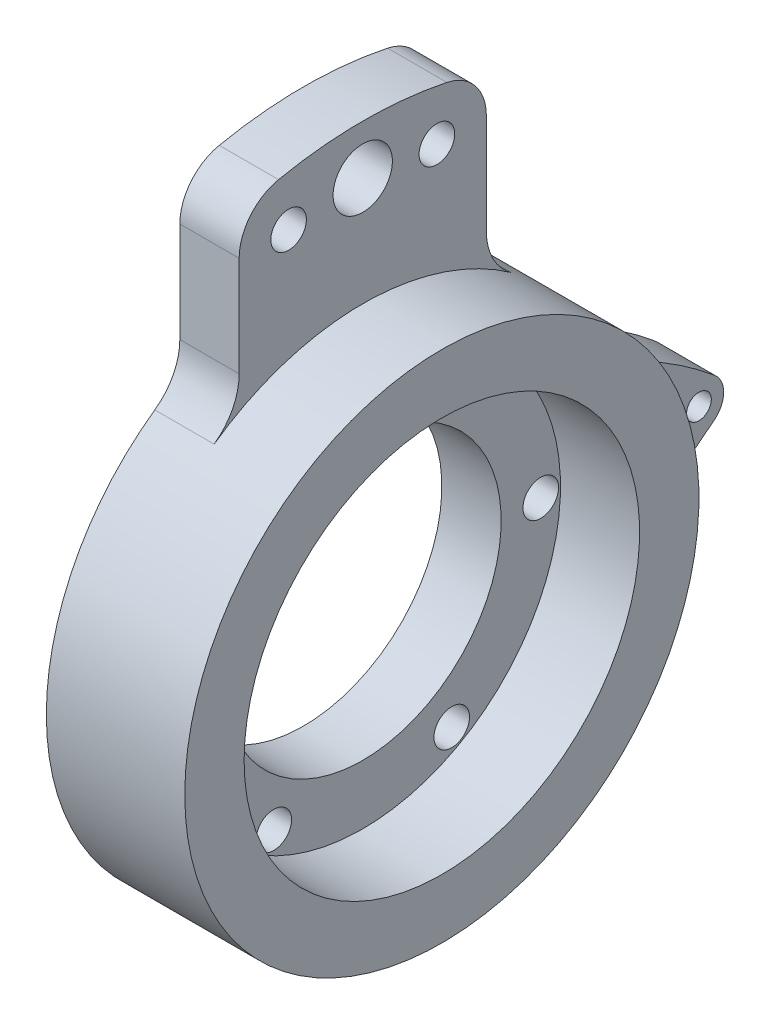
SolidWorks part; units mm, degrees
material "ABS"
ref_plane "Front Plane" through (0, 0, 0) normal (0, 0, 1) x (1, 0, 0)
ref_plane "Top Plane" through (0, 0, 0) normal (0, 1, 0) x (1, 0, 0)
ref_plane "Right Plane" through (0, 0, 0) normal (1, 0, 0) x (0, 0, -1)
sketch "Sketch1" plane through (0, 0, 0) normal (0, 0, 1) x (1, 0, 0)
  line L0 (0, 14) -> (6, 14)
  line L1 (6, 14) -> (6, 20)
  line L2 (6, 20) -> (14, 20)
  line L3 (14, 20) -> (14, 26)
  line L4 (14, 26) -> (0, 26)
  line L5 (0, 26) -> (0, 14)
  line L6 (-2.2572, 0) -> (2.2572, 0) construction
revolve "Revolve1" add sketch "Sketch1" angle 360 about L6
sketch "Sketch3" plane through (0, 0, 0) normal (1, 0, 0) x (0, 0, -1)
  arc A0 (24, -10) -> (26.0687, -7.8828) centre (27.6923, -11.5385) cw
  arc A1 (26.0687, -7.8828) -> (24, -10) centre (27.6923, -11.5385) ccw construction
  arc A2 (26.0687, -7.8828) -> (35.6111, -1.9116) centre (9.8328, 28.6739) ccw
  arc A5 (26.0687, -7.8828) -> (35.6111, -1.9116) centre (9.8328, 28.6739) ccw construction
  arc A6 (35.6111, -1.9116) -> (35.6111, 1.9116) centre (34, 0) ccw
  circle A7 centre (34, 0) radius 2.5 construction
  arc A8 (35.6111, 1.9116) -> (26.0687, 7.8828) centre (9.8328, -28.6739) ccw
  arc A9 (35.6111, 1.9116) -> (26.0687, 7.8828) centre (9.8328, -28.6739) ccw construction
  arc A10 (26.0687, 7.8828) -> (24, 10) centre (27.6923, 11.5385) cw
  arc A11 (24, 10) -> (26.0687, 7.8828) centre (27.6923, 11.5385) ccw construction
  arc A12 (24, 10) -> (24, -10) centre (0, 0) cw
  circle A13 centre (0, 0) radius 26 construction
extrude "Boss-Extrude2" add sketch "Sketch3" along normal up to vertex (6 mm away)
hole_wizard "M3 Clearance Hole1" positions "Sketch4" profile "Sketch6" tap size "M3" standard "ISO" end condition up to next
sketch "Sketch4" plane through (0, 0, 0) normal (-1, 0, 0) x (0, 0, 1)
  point P0 (-34, 0)
sketch "Sketch6" plane through (0, 0, -34) normal (0, 1, 0) x (0, 0, 1)
  line L0 (0, 0) -> (0, 6)
  line L1 (0, 6) -> (1.25, 6)
  line L2 (1.25, 6) -> (1.25, 0)
  line L5 (1.25, 0) -> (0, 0)
  line L11 (0, -6.35) -> (0, 107.95) construction
  dimension "Thru Tap Drill Dia." = 2.5
  dimension "Thru Tap Drill Depth" = 6
sketch "Sketch14" plane through (0, 0, 0) normal (1, 0, 0) x (0, 0, -1)
  line L0 (-12.5, 36.2319) -> (-12.5, 22.798) construction
  line L1 (12.5, 36.2319) -> (12.5, 22.798) construction
  line L2 (-12.5, 36.2319) -> (-12.5, 22.798)
  line L3 (12.5, 36.2319) -> (12.5, 22.798)
  arc A0 (24, 10) -> (24, -10) centre (0, 0) ccw construction
  circle A1 centre (0, 37) radius 3 construction
  arc A2 (12.5, 36.2319) -> (8.5135, 41.1281) centre (7.5, 36.2319) ccw construction
  arc A3 (8.5135, 41.1281) -> (-8.5135, 41.1281) centre (0, 0) ccw construction
  arc A4 (-8.5135, 41.1281) -> (-12.5, 36.2319) centre (-7.5, 36.2319) ccw construction
  arc A5 (12.5, 22.798) -> (-12.5, 22.798) centre (0, 0) ccw
  circle A6 centre (0, 37) radius 3
  arc A7 (12.5, 36.2319) -> (8.5135, 41.1281) centre (7.5, 36.2319) ccw
  arc A8 (8.5135, 41.1281) -> (-8.5135, 41.1281) centre (0, 0) ccw
  arc A9 (-8.5135, 41.1281) -> (-12.5, 36.2319) centre (-7.5, 36.2319) ccw
extrude "Boss-Extrude4" add sketch "Sketch14" along normal up to vertex (6 mm away)
hole_wizard "M3 Clearance Hole2" positions "Sketch7" profile "Sketch8" hole size "M3" standard "ISO" end condition up to next
sketch "Sketch7" plane through (0, 0, 0) normal (-1, 0, 0) x (0, 0, 1)
  point P0 (18, 0)
sketch "Sketch8" plane through (0, 0, 18) normal (0, 1, 0) x (0, 0, 1)
  line L0 (0, 0) -> (0, 6)
  line L1 (0, 6) -> (1.8, 6)
  line L2 (1.8, 6) -> (1.8, 0)
  line L5 (1.8, 0) -> (0, 0)
  line L11 (0, -6.35) -> (0, 107.95) construction
  dimension "Thru Hole Dia." = 3.6
  dimension "Thru Hole Depth" = 6
pattern_circular "CirPattern1" count 6 over 360 about axis through (0, 0, 0) along (1, 0, 0) of "M3 Clearance Hole2"
fillet "Fillet1" radius 6 2 edges at (3, 22.798, -12.5) (3, 22.798, 12.5)
hole_wizard "M3x0.5 Tapped Hole1" positions "Sketch15" profile "Sketch17" hole size "M3" standard "ANSI Metric" end condition up to next
sketch "Sketch15" plane through (0, 0, 0) normal (-1, 0, 0) x (0, 0, 1)
  point P0 (7.5, 36.2319)
  point P3 (-7.5, 36.2319)
sketch "Sketch17" plane through (0, 36.2319, 7.5) normal (0, 1, 0) x (0, 0, 1)
  line L0 (0, 0) -> (0, 6)
  line L1 (0, 6) -> (1.8, 6)
  line L2 (1.8, 6) -> (1.8, 0)
  line L5 (1.8, 0) -> (0, 0)
  line L11 (0, -6.35) -> (0, 107.95) construction
  dimension "Thru Hole Dia." = 3.6
  dimension "Thru Hole Depth" = 6
ref_plane "Plane1" [suppressed] through (13, 0, 0) normal (1, 0, 0) x (0, 0, -1)
mirror "Mirror1" [suppressed] about plane through (13, 0, 0) normal (1, 0, 0)
other "Intersect1" [suppressed]
delete or keep bodies "Body-Delete/Keep 1" [suppressed] type delete bodies bodies 113
